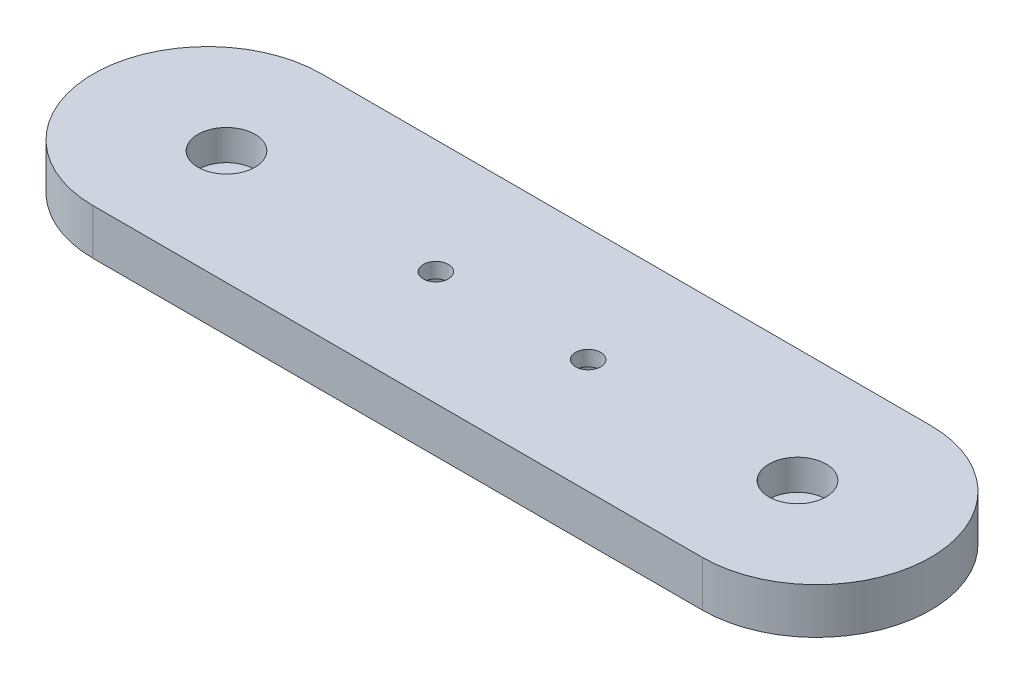
SolidWorks part; units mm, degrees
ref_plane "Front Plane" through (0, 0, 0) normal (0, 0, 1) x (1, 0, 0)
ref_plane "Top Plane" through (0, 0, 0) normal (0, 1, 0) x (1, 0, 0)
ref_plane "Right Plane" through (0, 0, 0) normal (1, 0, 0) x (0, 0, -1)
sketch "Sketch1" plane through (0, 0, 0) normal (0, 1, 0) x (1, 0, 0)
  line L5 (-40, 15) -> (40, 15)
  line L6 (-40, 15) -> (-40, -15) construction
  line L7 (-40, -15) -> (40, -15)
  line L8 (40, 15) -> (40, -15) construction
  line L9 (-40, 15) -> (40, -15) construction
  line L10 (-40, -15) -> (40, 15) construction
  arc A1 (-40, -15) -> (-40, 15) centre (-40, 0) cw
  arc A2 (40, 15) -> (40, -15) centre (40, 0) cw
  point P0 (0, 0)
  dimension "D1" = 30
  dimension "D2" = 80
extrude "Boss-Extrude1" add sketch "Sketch1" along normal blind 6
hole_wizard "M4 Tapped Hole3" positions "3DSketch2" profile "Sketch4" tap size "M4" standard "ISO"
sketch3d "3DSketch2"
  point P0 (37.5, 6, 0)
sketch "Sketch4" plane through (37.5, 6, 0) normal (1, 0, 0) x (0, 0, 1)
  line L0 (0, 0) -> (0, 12.4914)
  line L1 (0, 12.4914) -> (1.65, 11.5)
  line L2 (1.65, 11.5) -> (1.65, 0)
  line L5 (1.65, 0) -> (0, 0)
  line L10 (0, 12.4914) -> (-1.65, 11.5) construction
  line L11 (0, -6.35) -> (0, 107.95) construction
  dimension "Tap Drill Dia." = 3.3
  dimension "Tap Drill Depth" = 11.5
  dimension "Drill Angle" = 118
hole_wizard "M4 Tapped Hole5" positions "3DSketch9" profile "Sketch14" tap size "M4" standard "ISO" end condition through all
sketch3d "3DSketch9"
  point P0 (10, 6, 0)
sketch "Sketch14" plane through (10, 6, 0) normal (1, 0, 0) x (0, 0, 1)
  line L0 (0, 0) -> (0, 6)
  line L1 (0, 6) -> (1.65, 6)
  line L2 (1.65, 6) -> (1.65, 0)
  line L5 (1.65, 0) -> (0, 0)
  line L11 (0, -6.35) -> (0, 107.95) construction
  dimension "Thru Tap Drill Dia." = 3.3
  dimension "Thru Tap Drill Depth" = 6
pattern_linear "LPattern3" count 2 spacing 75 along (-1, 0, 0) of "M4 Tapped Hole3"
pattern_linear "LPattern4" count 2 spacing 20 along (-1, 0, 0) of "M4 Tapped Hole5"
sketch "Sketch15" plane through (0, 6, 0) normal (0, 1, 0) x (1, 0, 0)
  circle A0 centre (37.5, 0) radius 3.75
  circle A1 centre (-37.5, 0) radius 3.75
  dimension "D1" = 7.5
  dimension "D2" = 2
extrude "Cut-Extrude1" cut sketch "Sketch15" against normal blind 4
sketch "Sketch16" plane through (0, 0, 0) normal (0, -1, 0) x (1, 0, 0)
  circle A0 centre (-10, 0) radius 3.75
  circle A1 centre (10, 0) radius 3.75
  dimension "D1" = 7.5
  dimension "D2" = 7.5
extrude "Cut-Extrude3" cut sketch "Sketch16" against normal blind 4
